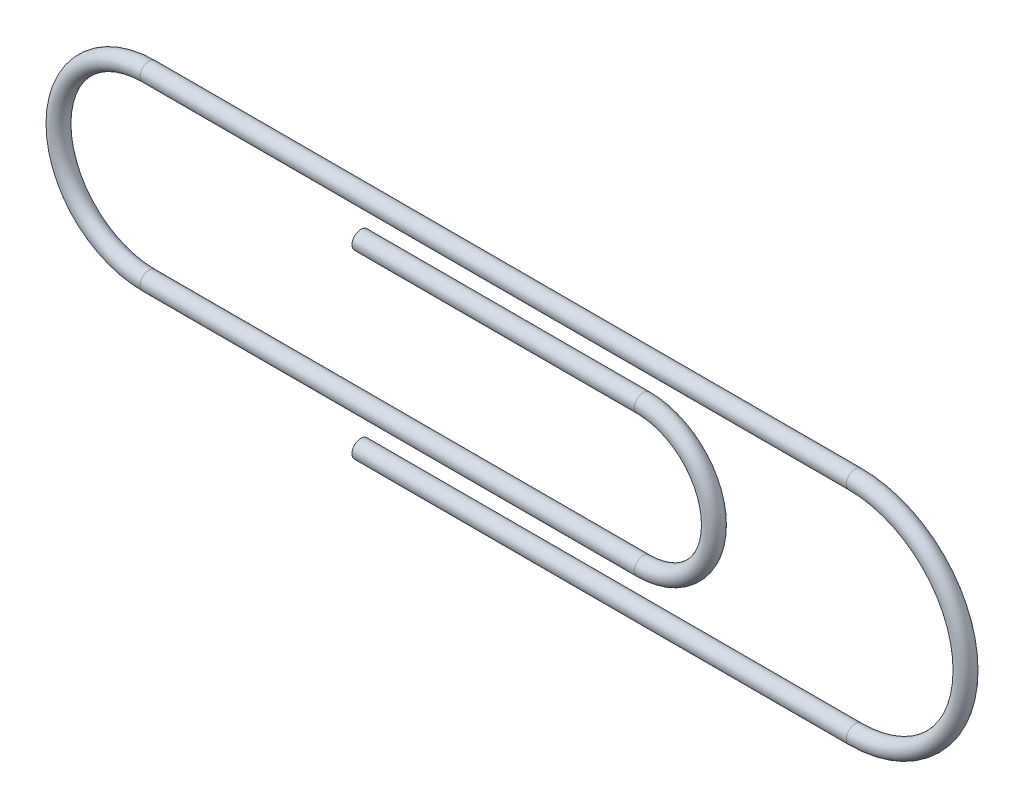
SolidWorks part; units mm, degrees
ref_plane "Front" through (0, 0, 0) normal (0, 0, 1) x (1, 0, 0)
ref_plane "Top" through (0, 0, 0) normal (0, 1, 0) x (1, 0, 0)
ref_plane "Right" through (0, 0, 0) normal (1, 0, 0) x (0, 0, -1)
sketch "Sketch1" plane through (0, 0, 0) normal (0, 0, 1) x (1, 0, 0)
  line L0 (0, 0) -> (8, 0)
  line L1 (8, -4) -> (-6, -4)
  line L2 (-6, 1.125) -> (14, 1.125)
  line L3 (14, -5.125) -> (0, -5.125)
  arc A0 (8, 0) -> (8, -4) centre (8, -2) cw
  arc A1 (-6, -4) -> (-6, 1.125) centre (-6, -1.4375) cw
  arc A2 (14, 1.125) -> (14, -5.125) centre (14, -2) cw
  dimension "D1" = 14
  dimension "D2" = 1.125
  dimension "D3" = 1.125
  dimension "D4" = 6
  dimension "D5" = 6
  dimension "D6" = 4
ref_plane "Plane1" through (0, 0, 0) normal (1, 0, 0) x (0, 0, -1)
sketch "Sketch2" plane through (0, 0, 0) normal (1, 0, 0) x (0, 0, -1)
  circle A0 centre (0, 0) radius 0.25
  dimension "D1" = 0.5
sweep "Sweep2" add profiles "Sketch2" path "Sketch1"
